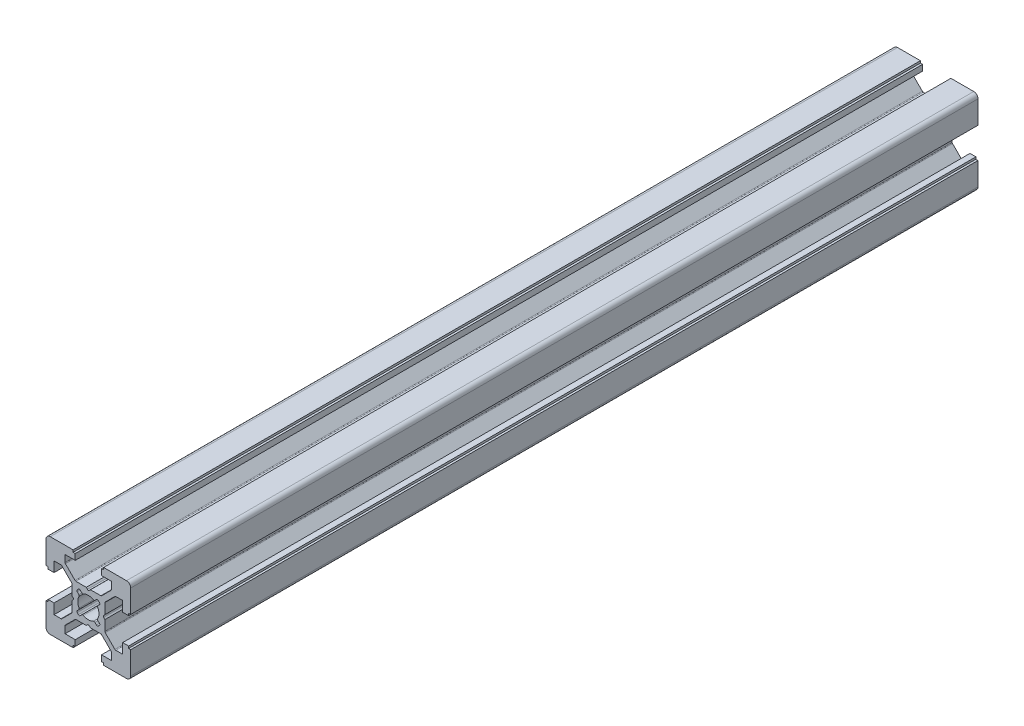
SolidWorks part; units mm, degrees
material "6063-O"
ref_plane "Спереди" through (0, 0, 0) normal (0, 0, 1) x (1, 0, 0)
ref_plane "Сверху" through (0, 0, 0) normal (0, 1, 0) x (1, 0, 0)
ref_plane "Справа" through (0, 0, 0) normal (1, 0, 0) x (0, 0, -1)
sketch "Эскиз2" plane through (0, 0, 0) normal (0, 0, 1) x (1, 0, 0)
  line L0 (3.9, -0.5) -> (3.9, -2.9272)
  line L1 (3.6121, -0.2121) -> (3.9, -0.5)
  line L2 (3.6121, 0.2121) -> (3.9, 0.5)
  line L3 (3.9, 2.9272) -> (3.9, 0.5)
  line L4 (3.9879, 3.1393) -> (6.2607, 5.4121)
  line L5 (6.4728, 5.5) -> (8.1, 5.5)
  line L6 (8.1, 3.1) -> (8.1, 5.5)
  line L7 (9.5, 3.1) -> (8.1, 3.1)
  line L8 (9.5, 3.6) -> (9.5, 3.1)
  line L9 (10, 3.6) -> (9.5, 3.6)
  line L10 (10, 9) -> (10, 3.6)
  line L11 (9, 10) -> (3.6, 10)
  line L12 (3.6, 9.5) -> (3.6, 10)
  line L13 (3.1, 9.5) -> (3.6, 9.5)
  line L14 (3.1, 9.5) -> (3.1, 8.1)
  line L15 (3.1, 8.1) -> (5.5, 8.1)
  line L16 (5.5, 8.1) -> (5.5, 6.4728)
  line L17 (3.1393, 3.9879) -> (5.4121, 6.2607)
  line L18 (0.5, 3.9) -> (2.9272, 3.9)
  line L19 (0.2121, 3.6121) -> (0.5, 3.9)
  line L20 (-0.2121, 3.6121) -> (-0.5, 3.9)
  line L21 (-2.9272, 3.9) -> (-0.5, 3.9)
  line L22 (-5.4121, 6.2607) -> (-3.1393, 3.9879)
  line L23 (-5.5, 6.4728) -> (-5.5, 8.1)
  line L24 (-3.1, 8.1) -> (-5.5, 8.1)
  line L25 (-3.1, 9.5) -> (-3.1, 8.1)
  line L26 (-3.1, 9.5) -> (-3.6, 9.5)
  line L27 (-3.6, 9.5) -> (-3.6, 10)
  line L28 (-9, 10) -> (-3.6, 10)
  line L29 (-10, 9) -> (-10, 3.6)
  line L30 (-10, 3.6) -> (-9.5, 3.6)
  line L31 (-9.5, 3.6) -> (-9.5, 3.1)
  line L32 (-9.5, 3.1) -> (-8.1, 3.1)
  line L33 (-8.1, 3.1) -> (-8.1, 5.5)
  line L34 (-8.1, 5.5) -> (-6.4728, 5.5)
  line L35 (-3.9879, 3.1393) -> (-6.2607, 5.4121)
  line L36 (-3.9, 2.9272) -> (-3.9, 0.5)
  line L37 (-3.6121, 0.2121) -> (-3.9, 0.5)
  line L38 (-3.6121, -0.2121) -> (-3.9, -0.5)
  line L39 (-3.9, -0.5) -> (-3.9, -2.9272)
  line L40 (-6.2607, -5.4121) -> (-3.9879, -3.1393)
  line L41 (-6.4728, -5.5) -> (-8.1, -5.5)
  line L42 (-8.1, -3.1) -> (-8.1, -5.5)
  line L43 (-9.5, -3.1) -> (-8.1, -3.1)
  line L44 (-9.5, -3.6) -> (-9.5, -3.1)
  line L45 (-10, -3.6) -> (-9.5, -3.6)
  line L46 (-10, -3.6) -> (-10, -9)
  line L47 (-9, -10) -> (-3.6, -10)
  line L48 (-3.6, -9.5) -> (-3.6, -10)
  line L49 (-3.1, -9.5) -> (-3.6, -9.5)
  line L50 (-3.1, -9.5) -> (-3.1, -8.1)
  line L51 (-3.1, -8.1) -> (-5.5, -8.1)
  line L52 (-5.5, -8.1) -> (-5.5, -6.4728)
  line L53 (-3.1393, -3.9879) -> (-5.4121, -6.2607)
  line L54 (-2.9272, -3.9) -> (-0.5, -3.9)
  line L55 (-0.2121, -3.6121) -> (-0.5, -3.9)
  line L56 (0.2121, -3.6121) -> (0.5, -3.9)
  line L57 (0.5, -3.9) -> (2.9272, -3.9)
  line L58 (5.4121, -6.2607) -> (3.1393, -3.9879)
  line L59 (5.5, -8.1) -> (5.5, -6.4728)
  line L60 (3.1, -8.1) -> (5.5, -8.1)
  line L61 (3.1, -9.5) -> (3.1, -8.1)
  line L62 (3.1, -9.5) -> (3.6, -9.5)
  line L63 (3.6, -9.5) -> (3.6, -10)
  line L64 (3.6, -10) -> (9, -10)
  line L65 (10, -3.6) -> (10, -9)
  line L66 (10, -3.6) -> (9.5, -3.6)
  line L67 (9.5, -3.6) -> (9.5, -3.1)
  line L68 (9.5, -3.1) -> (8.1, -3.1)
  line L69 (8.1, -3.1) -> (8.1, -5.5)
  line L70 (6.4728, -5.5) -> (8.1, -5.5)
  line L71 (3.9879, -3.1393) -> (6.2607, -5.4121)
  line L72 (-1.9092, 2.6163) -> (-1.5438, 2.2509)
  line L73 (1.9092, 2.6163) -> (1.5438, 2.2509)
  line L74 (2.6163, 2.3335) -> (2.3335, 2.6163)
  line L75 (2.6163, 1.9092) -> (2.2509, 1.5438)
  line L76 (2.2509, -1.5438) -> (2.6163, -1.9092)
  line L77 (2.3335, -2.6163) -> (2.6163, -2.3335)
  line L78 (1.5438, -2.2509) -> (1.9092, -2.6163)
  line L79 (-1.5438, -2.2509) -> (-1.9092, -2.6163)
  line L80 (-2.6163, -2.3335) -> (-2.3335, -2.6163)
  line L81 (-2.2509, -1.5438) -> (-2.6163, -1.9092)
  line L82 (-2.6163, 1.9092) -> (-2.2509, 1.5438)
  line L83 (-2.3335, 2.6163) -> (-2.6163, 2.3335)
  arc A0 (3.9, -2.9272) -> (3.9879, -3.1393) centre (4.2, -2.9272) ccw
  arc A1 (3.6121, 0.2121) -> (3.6121, -0.2121) centre (3.8243, 0) ccw
  arc A2 (3.9879, 3.1393) -> (3.9, 2.9272) centre (4.2, 2.9272) ccw
  arc A3 (6.4728, 5.5) -> (6.2607, 5.4121) centre (6.4728, 5.2) ccw
  arc A4 (10, 9) -> (9, 10) centre (9, 9) ccw
  arc A5 (5.4121, 6.2607) -> (5.5, 6.4728) centre (5.2, 6.4728) ccw
  arc A6 (2.9272, 3.9) -> (3.1393, 3.9879) centre (2.9272, 4.2) ccw
  arc A7 (-0.2121, 3.6121) -> (0.2121, 3.6121) centre (0, 3.8243) ccw
  arc A8 (-3.1393, 3.9879) -> (-2.9272, 3.9) centre (-2.9272, 4.2) ccw
  arc A9 (-5.5, 6.4728) -> (-5.4121, 6.2607) centre (-5.2, 6.4728) ccw
  arc A10 (-9, 10) -> (-10, 9) centre (-9, 9) ccw
  arc A11 (-6.2607, 5.4121) -> (-6.4728, 5.5) centre (-6.4728, 5.2) ccw
  arc A12 (-3.9, 2.9272) -> (-3.9879, 3.1393) centre (-4.2, 2.9272) ccw
  arc A13 (-3.6121, -0.2121) -> (-3.6121, 0.2121) centre (-3.8243, 0) ccw
  arc A14 (-3.9879, -3.1393) -> (-3.9, -2.9272) centre (-4.2, -2.9272) ccw
  arc A15 (-6.4728, -5.5) -> (-6.2607, -5.4121) centre (-6.4728, -5.2) ccw
  arc A16 (-10, -9) -> (-9, -10) centre (-9, -9) ccw
  arc A17 (-5.4121, -6.2607) -> (-5.5, -6.4728) centre (-5.2, -6.4728) ccw
  arc A18 (-2.9272, -3.9) -> (-3.1393, -3.9879) centre (-2.9272, -4.2) ccw
  arc A19 (0.2121, -3.6121) -> (-0.2121, -3.6121) centre (0, -3.8243) ccw
  arc A20 (3.1393, -3.9879) -> (2.9272, -3.9) centre (2.9272, -4.2) ccw
  arc A21 (5.5, -6.4728) -> (5.4121, -6.2607) centre (5.2, -6.4728) ccw
  arc A22 (9, -10) -> (10, -9) centre (9, -9) ccw
  arc A23 (6.2607, -5.4121) -> (6.4728, -5.5) centre (6.4728, -5.2) ccw
  arc A24 (-1.5438, 2.2509) -> (-1.189, 2.1992) centre (-1.3317, 2.4631) ccw
  arc A25 (1.189, 2.1992) -> (-1.189, 2.1992) centre (0, 0) ccw
  arc A26 (1.189, 2.1992) -> (1.5438, 2.2509) centre (1.3317, 2.4631) ccw
  arc A27 (2.3335, 2.6163) -> (1.9092, 2.6163) centre (2.1213, 2.4042) ccw
  arc A28 (2.6163, 1.9092) -> (2.6163, 2.3335) centre (2.4042, 2.1213) ccw
  arc A29 (2.2509, 1.5438) -> (2.1992, 1.189) centre (2.4631, 1.3317) ccw
  arc A30 (2.1992, -1.189) -> (2.1992, 1.189) centre (0, 0) ccw
  arc A31 (2.1992, -1.189) -> (2.2509, -1.5438) centre (2.4631, -1.3317) ccw
  arc A32 (2.6163, -2.3335) -> (2.6163, -1.9092) centre (2.4042, -2.1213) ccw
  arc A33 (1.9092, -2.6163) -> (2.3335, -2.6163) centre (2.1213, -2.4042) ccw
  arc A34 (1.5438, -2.2509) -> (1.189, -2.1992) centre (1.3317, -2.4631) ccw
  arc A35 (-1.189, -2.1992) -> (1.189, -2.1992) centre (0, 0) ccw
  arc A36 (-1.189, -2.1992) -> (-1.5438, -2.2509) centre (-1.3317, -2.4631) ccw
  arc A37 (-2.3335, -2.6163) -> (-1.9092, -2.6163) centre (-2.1213, -2.4042) ccw
  arc A38 (-2.6163, -1.9092) -> (-2.6163, -2.3335) centre (-2.4042, -2.1213) ccw
  arc A39 (-2.2509, -1.5438) -> (-2.1992, -1.189) centre (-2.4631, -1.3317) ccw
  arc A40 (-2.1992, 1.189) -> (-2.1992, -1.189) centre (0, 0) ccw
  arc A41 (-2.1992, 1.189) -> (-2.2509, 1.5438) centre (-2.4631, 1.3317) ccw
  arc A42 (-2.6163, 2.3335) -> (-2.6163, 1.9092) centre (-2.4042, 2.1213) ccw
  arc A43 (-1.9092, 2.6163) -> (-2.3335, 2.6163) centre (-2.1213, 2.4042) ccw
extrude "Бобышка-Вытянуть1" add sketch "Эскиз2" along normal blind 200
